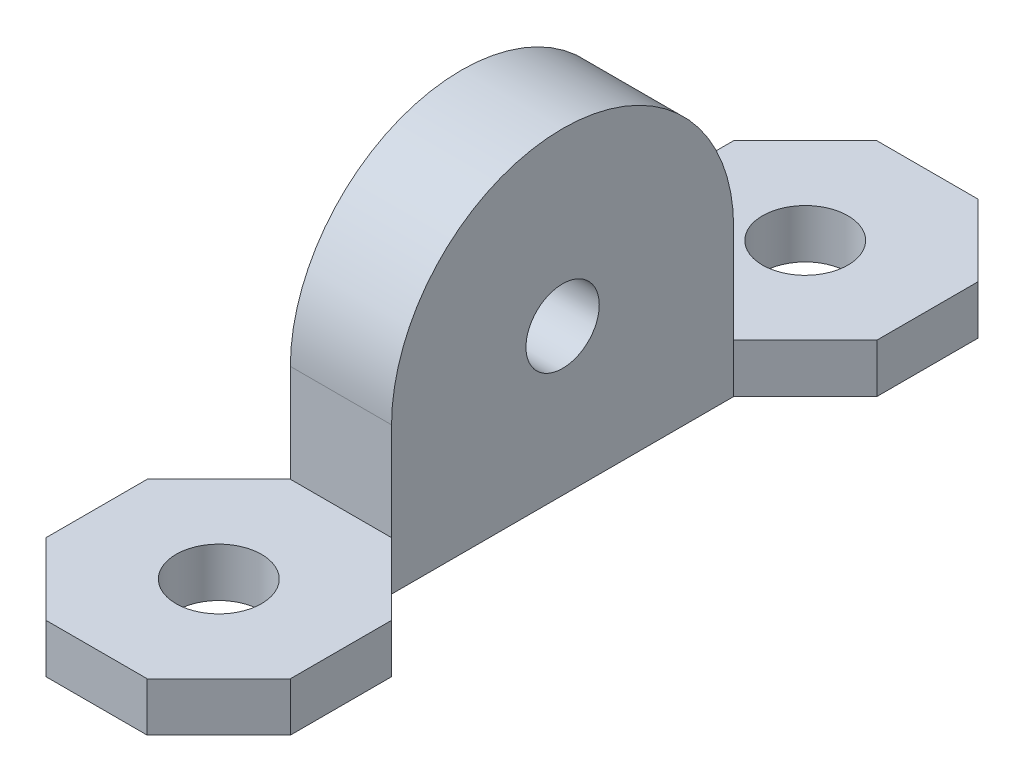
SolidWorks part; units mm, degrees
material "ABS"
ref_plane "Plan de face" through (0, 0, 0) normal (0, 0, 1) x (1, 0, 0)
ref_plane "Plan de dessus" through (0, 0, 0) normal (0, 1, 0) x (1, 0, 0)
ref_plane "Plan de droite" through (0, 0, 0) normal (1, 0, 0) x (0, 0, -1)
sketch "Esquisse1" plane through (0, 0, 0) normal (0, 1, 0) x (1, 0, 0)
  line L0 (1.7953, 13.277) -> (-2.3468, 13.277)
  line L1 (-2.3468, 13.277) -> (-5.2758, 10.3481)
  line L2 (-5.2758, 10.3481) -> (-5.2758, 6.206)
  line L3 (-5.2758, 6.206) -> (-2.3468, 3.277)
  line L5 (1.7953, 3.277) -> (4.7242, 6.206)
  line L6 (4.7242, 6.206) -> (4.7242, 10.3481)
  line L7 (4.7242, 10.3481) -> (1.7953, 13.277)
  line L8 (-2.3468, 3.277) -> (-2.3468, -10.723)
  line L9 (-2.3468, -10.723) -> (-5.2758, -13.6519)
  line L10 (-5.2758, -13.6519) -> (-5.2758, -17.794)
  line L11 (-5.2758, -17.794) -> (-2.3468, -20.723)
  line L12 (-2.3468, -20.723) -> (1.7953, -20.723)
  line L13 (1.7953, -20.723) -> (4.7242, -17.794)
  line L14 (4.7242, -17.794) -> (4.7242, -13.6519)
  line L15 (4.7242, -13.6519) -> (1.7953, -10.723)
  line L16 (1.7953, -10.723) -> (1.7953, 3.277)
  dimension "D1" = 10
  dimension "D2" = 34
extrude "Boss.-Extru.1" add sketch "Esquisse1" along normal blind 2
sketch "Esquisse3" plane through (0, 0, 0) normal (1, 0, 0) x (0, 0, -1)
  line L0 (-10.723, 0) -> (-10.723, 6)
  line L1 (3.277, 6) -> (3.277, 0)
  line L2 (-10.723, 0) -> (3.277, 0) construction
  line L3 (3.277, 0) -> (-10.723, 0)
  arc A0 (-10.723, 6) -> (3.277, 6) centre (-3.723, 6) cw
  dimension "D1" = 6
extrude "Boss.-Extru.2" add sketch "Esquisse3" along normal up to surface and the other way up to surface up to face at (1.7953, 1, 3.723) other way up to face at (-2.3468, 1, 3.723)
sketch "Esquisse6" plane through (1.7953, 0, 0) normal (1, 0, 0) x (0, 0, -1)
  circle A0 centre (-3.723, 6) radius 1.5
extrude "Enlèv. mat.-Extru.3" cut sketch "Esquisse6" against normal through all
sketch "Esquisse7" plane through (0, 2, 0) normal (0, 1, 0) x (1, 0, 0)
  line L0 (-5.2758, -13.6519) -> (-5.2758, -17.794) construction
  line L1 (-2.3468, -20.723) -> (1.7953, -20.723) construction
  line L2 (-5.2758, 10.3481) -> (-5.2758, 6.206) construction
  line L3 (1.7953, 13.277) -> (-2.3468, 13.277) construction
  circle A0 centre (-0.2758, -15.723) radius 1.75
  circle A1 centre (-0.2758, 8.277) radius 1.75
  point P8 (-5.2758, -15.723)
  point P11 (-0.2758, -20.723)
  point P14 (-5.2758, 8.277)
  point P17 (-0.2758, 13.277)
  dimension "D1" = 3.5
  dimension "D2" = 3.5
extrude "Enlèv. mat.-Extru.4" cut sketch "Esquisse7" against normal through all
